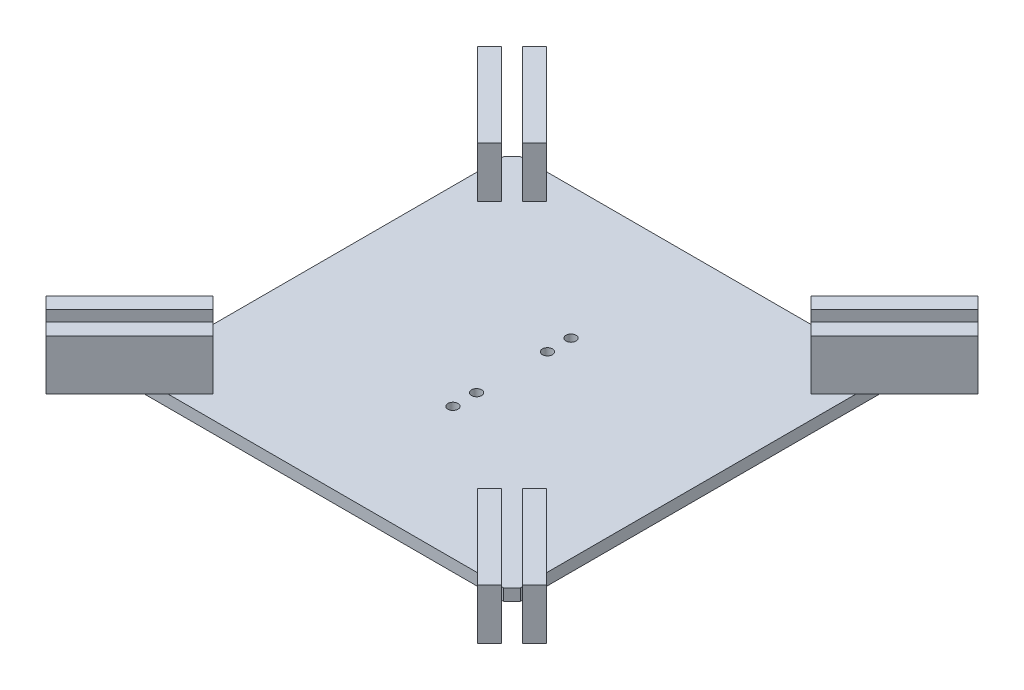
SolidWorks part; units mm, degrees
ref_plane "Front Plane" through (0, 0, 0) normal (0, 0, 1) x (1, 0, 0)
ref_plane "Top Plane" through (0, 0, 0) normal (0, 1, 0) x (1, 0, 0)
ref_plane "Right Plane" through (0, 0, 0) normal (1, 0, 0) x (0, 0, -1)
sketch "Sketch2" plane through (0, 0, 0) normal (0, 1, 0) x (1, 0, 0)
  line L1 (-56.5685, -56.5685) -> (56.5685, -56.5685)
  line L2 (-56.5685, -56.5685) -> (-56.5685, 56.5685)
  line L3 (-56.5685, 56.5685) -> (56.5685, 56.5685)
  line L4 (56.5685, -56.5685) -> (56.5685, 56.5685)
  line L5 (-56.5685, -56.5685) -> (56.5685, 56.5685) construction
  line L6 (-56.5685, 56.5685) -> (56.5685, -56.5685) construction
  point P0 (0, 0)
  dimension "D1" = 160
extrude "Boss-Extrude1" add sketch "Sketch2" along normal blind 3.5
chamfer "Chamfer1" distance 2.5 angle 45 4 edges at (-56.5685, 1.75, 56.5685) (56.5685, 1.75, 56.5685) (56.5685, 1.75, -56.5685) (-56.5685, 1.75, -56.5685)
sketch "Sketch3" plane through (0, 0, 0) normal (0, -1, 0) x (1, 0, 0)
  line L0 (0, 0) -> (-35355.3391, 35355.3391) construction
  line L1 (0, 0) -> (35355.3391, 35355.3391) construction
  line L2 (-3.5355, 6.7175) -> (0, 3.182)
  line L3 (-3.5355, 6.7175) -> (17.6777, 27.9307)
  line L4 (0, 3.182) -> (21.2132, 24.3952)
  line L5 (17.6777, 27.9307) -> (21.2132, 24.3952)
  line L6 (3.182, 0) -> (24.3952, 21.2132)
  line L7 (27.9307, 17.6777) -> (24.3952, 21.2132)
  line L8 (54.0685, 56.5685) -> (-54.0685, 56.5685)
  line L9 (-54.0685, 56.5685) -> (-56.5685, 54.0685)
  line L10 (-56.5685, 54.0685) -> (-56.5685, -54.0685)
  line L11 (-56.5685, -54.0685) -> (-54.0685, -56.5685)
  line L12 (-54.0685, -56.5685) -> (54.0685, -56.5685)
  line L13 (54.0685, -56.5685) -> (56.5685, -54.0685)
  line L14 (56.5685, -54.0685) -> (56.5685, 54.0685)
  line L15 (56.5685, 54.0685) -> (54.0685, 56.5685)
  line L16 (54.0685, 56.5685) -> (-54.0685, 56.5685)
  line L17 (-54.0685, 56.5685) -> (-56.5685, 54.0685)
  line L18 (-56.5685, 54.0685) -> (-56.5685, -54.0685)
  line L19 (-56.5685, -54.0685) -> (-54.0685, -56.5685)
  line L20 (-54.0685, -56.5685) -> (54.0685, -56.5685)
  line L21 (54.0685, -56.5685) -> (56.5685, -54.0685)
  line L22 (56.5685, -54.0685) -> (56.5685, 54.0685)
  line L23 (56.5685, 54.0685) -> (54.0685, 56.5685)
  line L24 (6.7175, -3.5355) -> (27.9307, 17.6777)
  line L25 (6.7175, -3.5355) -> (3.182, 0)
  line L26 (6.7175, 3.5355) -> (3.182, 0)
  line L27 (6.7175, 3.5355) -> (27.9307, -17.6777)
  line L28 (27.9307, -17.6777) -> (24.3952, -21.2132)
  line L29 (3.182, 0) -> (24.3952, -21.2132)
  line L30 (0, -3.182) -> (21.2132, -24.3952)
  line L31 (17.6777, -27.9307) -> (21.2132, -24.3952)
  line L32 (-3.5355, -6.7175) -> (17.6777, -27.9307)
  line L33 (-3.5355, -6.7175) -> (0, -3.182)
  line L34 (3.5355, -6.7175) -> (0, -3.182)
  line L35 (3.5355, -6.7175) -> (-17.6777, -27.9307)
  line L36 (-17.6777, -27.9307) -> (-21.2132, -24.3952)
  line L37 (0, -3.182) -> (-21.2132, -24.3952)
  line L38 (-3.182, 0) -> (-24.3952, -21.2132)
  line L39 (-27.9307, -17.6777) -> (-24.3952, -21.2132)
  line L40 (-6.7175, 3.5355) -> (-27.9307, -17.6777)
  line L41 (-6.7175, 3.5355) -> (-3.182, 0)
  line L42 (-6.7175, -3.5355) -> (-3.182, 0)
  line L43 (-6.7175, -3.5355) -> (-27.9307, 17.6777)
  line L44 (-27.9307, 17.6777) -> (-24.3952, 21.2132)
  line L45 (-3.182, 0) -> (-24.3952, 21.2132)
  line L46 (0, 3.182) -> (-21.2132, 24.3952)
  line L47 (-17.6777, 27.9307) -> (-21.2132, 24.3952)
  line L48 (3.5355, 6.7175) -> (-17.6777, 27.9307)
  line L49 (3.5355, 6.7175) -> (0, 3.182)
  point P10 (-55.3185, 55.3185)
  point P15 (55.3185, 55.3185)
  dimension "D1" = 0
extrude "Boss-Extrude3" add sketch "Sketch3" along normal blind 15 contours L46 L47 L48 L49 | L2 L3 L5 L4 | L6 L7 L24 L25 | L26 L29 L28 L27 | L34 L37 L36 L35 | L30 L31 L32 L33 | L42 L45 L44 L43 | L38 L39 L40 L41
sketch "Sketch6" plane through (0, 3.5, 0) normal (0, 1, 0) x (1, 0, 0)
  line L0 (0, 0) -> (-35355.3391, 35355.3391) construction
  line L1 (-54.0685, 56.5685) -> (-56.5685, 54.0685) construction
  line L2 (0, 0) -> (35355.3391, 35355.3391) construction
  line L3 (56.5685, 54.0685) -> (54.0685, 56.5685) construction
  line L4 (-66.9493, 70.1313) -> (-42.2006, 45.3826)
  line L5 (-66.9493, 70.1313) -> (-63.4138, 73.6668)
  line L6 (-42.2006, 45.3826) -> (-38.6651, 48.9181)
  line L7 (-63.4138, 73.6668) -> (-38.6651, 48.9181)
  line L8 (-45.3826, 42.2006) -> (-48.9181, 38.6651)
  line L9 (-73.6668, 63.4138) -> (-48.9181, 38.6651)
  line L10 (-70.1313, 66.9493) -> (-73.6668, 63.4138)
  line L11 (-70.1313, 66.9493) -> (-45.3826, 42.2006)
  point P5 (-55.3185, 55.3185)
  point P10 (55.3185, 55.3185)
  dimension "D1" = 4.5
  dimension "D2" = 5
  dimension "D3" = 35
extrude "Boss-Extrude5" add sketch "Sketch6" along normal blind 15
pattern_circular "CirPattern11" count 4 over 360 about axis through (0.5111, 0, 0.5111) along (0, 1, 0) of "Boss-Extrude5"
sketch "Sketch8" plane through (0, 3.5, 0) normal (0, 1, 0) x (1, 0, 0)
  line L0 (0, -10.5) -> (0, 10.5) construction
  line L5 (8.5, 10.5) -> (-8.5, 10.5) construction
  line L7 (8.5, -10.5) -> (-8.5, -10.5) construction
  line L9 (0, -19) -> (0, 19) construction
  circle A0 centre (0, 10.5) radius 1.5
  circle A1 centre (0, -10.5) radius 1.5
  circle A2 centre (7, 10.5) radius 1.5
  circle A3 centre (0, 17.5) radius 1.5
  circle A4 centre (-7, 10.5) radius 1.5
  circle A5 centre (7, -10.5) radius 1.5
  circle A6 centre (-7, -10.5) radius 1.5
  circle A7 centre (0, -17.5) radius 1.5
  circle A8 centre (0, 3.5) radius 1.5
  circle A9 centre (0, -3.5) radius 1.5
  point P8 (0, 0)
  dimension "D3" = 3
  dimension "D4" = 35
  dimension "D7" = 14
  dimension "D2" = 21
  dimension "D5" = 14
  dimension "D6" = 14
extrude "Cut-Extrude3" cut sketch "Sketch8" against normal up to surface (18.5 mm away) contours A7 | A1 | A3 | A0
sketch "Sketch9" plane through (0, 0, 0) normal (0, -1, 0) x (1, 0, 0)
  circle A0 centre (0, 10.5) radius 3.6032
  circle A1 centre (0, -10.5) radius 3.6032
extrude "Cut-Extrude4" cut sketch "Sketch9" along normal blind 10
